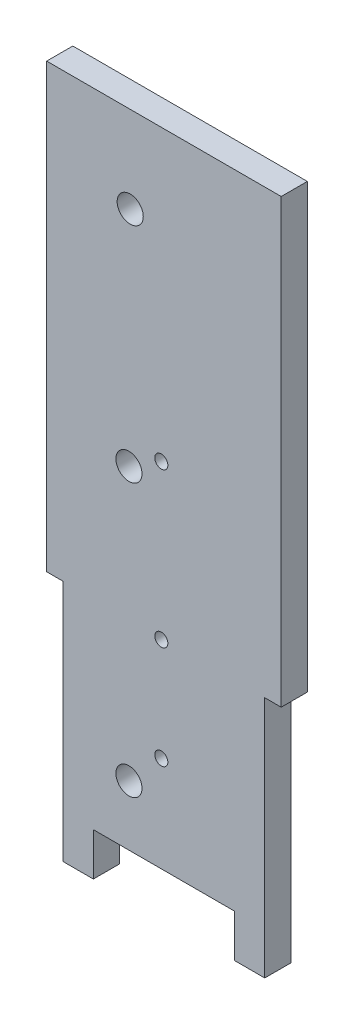
SolidWorks part; units mm, degrees
material "Low Carbon Steel"
ref_plane "Front Plane" through (0, 0, 0) normal (0, 0, 1) x (1, 0, 0)
ref_plane "Top Plane" through (0, 0, 0) normal (0, 1, 0) x (1, 0, 0)
ref_plane "Right Plane" through (0, 0, 0) normal (1, 0, 0) x (0, 0, -1)
sketch "Sketch1" plane through (0, 0, 0) normal (0, 0, 1) x (1, 0, 0)
  line L1 (-245, 0) -> (245, 0)
  line L2 (-245, 0) -> (-245, 590)
  line L3 (-285, 1665) -> (285, 1665)
  line L4 (245, 0) -> (245, 590)
  line L7 (-245, 590) -> (-285, 590)
  line L8 (-285, 1665) -> (-285, 590)
  line L11 (245, 590) -> (285, 590)
  line L12 (285, 1665) -> (285, 590)
  dimension "D1" = 40
  dimension "D2" = 40
  dimension "D3" = 570
  dimension "D4" = 1665
  dimension "D5" = 1075
extrude "Boss-Extrude1" add sketch "Sketch1" along normal blind 63.5
sketch "Sketch2" plane through (0, 0, 0) normal (0, 0, -1) x (-1, 0, 0)
  line L0 (245, 0) -> (-245, 0) construction
  line L1 (-171.5, 0) -> (171.5, 0)
  line L2 (-171.5, 0) -> (-171.5, 104)
  line L3 (-171.5, 104) -> (171.5, 104)
  line L4 (171.5, 0) -> (171.5, 104)
  dimension "D1" = 104
  dimension "D2" = 343
extrude "Cut-Extrude1" cut sketch "Sketch2" against normal through all
sketch "Sketch3" plane through (0, 0, 63.5) normal (0, 0, 1) x (1, 0, 0)
  line L0 (285, 1665) -> (-285, 1665) construction
  line L1 (-285, 1665) -> (-285, 590) construction
  circle A0 centre (-82, 1455) radius 31.75
  dimension "D1" = 63.5
  dimension "D2" = 210
  dimension "D3" = 203
extrude "Cut-Extrude2" cut sketch "Sketch3" against normal through all
sketch "Sketch4" plane through (0, 0, 63.5) normal (0, 0, 1) x (1, 0, 0)
  line L0 (-85, 911.9875) -> (-85, 250) construction
  line L1 (-245, 0) -> (-171.5, 0) construction
  circle A0 centre (-85, 250) radius 31.75
  circle A1 centre (-85, 911.9875) radius 31.75
  dimension "D2" = 63.5
  dimension "D1" = 661.9875
  dimension "D3" = 85
  dimension "D4" = 250
extrude "Cut-Extrude3" cut sketch "Sketch4" against normal through all
sketch "Sketch5" plane through (0, 0, 63.5) normal (0, 0, 1) x (1, 0, 0)
  line L0 (-6.4, 961.5) -> (-6.4, 586.5) construction
  line L1 (-6.4, 586.5) -> (-6.4, 336.5) construction
  line L2 (-245, 590) -> (-245, 0) construction
  line L3 (171.5, 0) -> (245, 0) construction
  circle A0 centre (-6.4, 336.5) radius 15.875
  circle A1 centre (-6.4, 586.5) radius 15.875
  circle A2 centre (-6.4, 961.5) radius 15.875
  dimension "D1" = 31.75
  dimension "D5" = 336.5
  dimension "D2" = 250
  dimension "D3" = 375
  dimension "D4" = 238.6
extrude "Cut-Extrude4" cut sketch "Sketch5" against normal through all
other "Freeze***"
